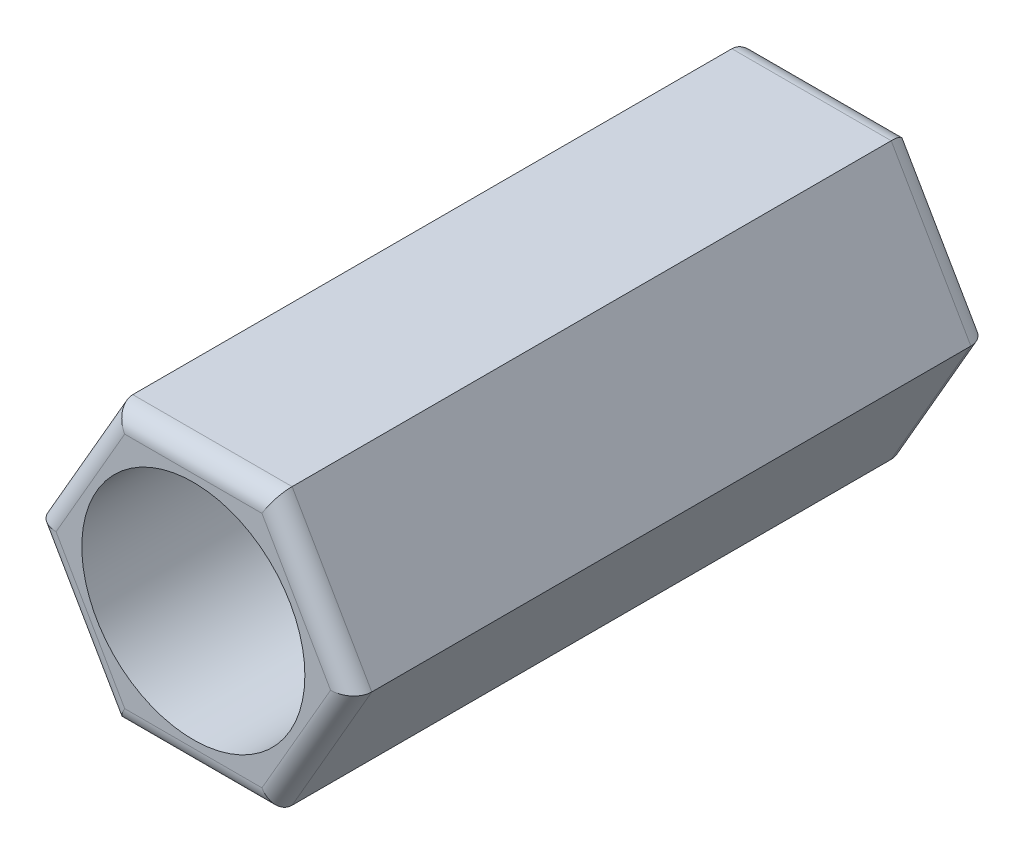
SolidWorks part; units mm, degrees
ref_plane "Front Plane" through (0, 0, 0) normal (0, 0, 1) x (1, 0, 0)
ref_plane "Top Plane" through (0, 0, 0) normal (0, 1, 0) x (1, 0, 0)
ref_plane "Right Plane" through (0, 0, 0) normal (1, 0, 0) x (0, 0, -1)
sketch "Sketch1" plane through (0, 0, 0) normal (0, 0, 1) x (1, 0, 0)
  line L1 (2.5, 0) -> (1.25, 2.1651)
  line L2 (1.25, 2.1651) -> (-1.25, 2.1651)
  line L3 (-1.25, 2.1651) -> (-2.5, 0)
  line L4 (-2.5, 0) -> (-1.25, -2.1651)
  line L5 (-1.25, -2.1651) -> (1.25, -2.1651)
  line L6 (1.25, -2.1651) -> (2.5, 0)
  circle A0 centre (0, 0) radius 2.1651 construction
  circle A1 centre (0, 0) radius 1.75
  dimension "D2" = 3.5
  dimension "D1" = 5
extrude "Boss-Extrude1" add sketch "Sketch1" along normal blind 10
fillet "Fillet5" radius 0.3 6 edges at (1.875, -1.0825, 10) (1.875, 1.0825, 10) (0, 2.1651, 10) (-1.875, 1.0825, 10) (-1.875, -1.0825, 10) (0, -2.1651, 10)
fillet "Fillet6" radius 0.3 6 edges at (0, -2.1651, 0) (-1.875, -1.0825, 0) (-1.875, 1.0825, 0) (1.875, 1.0825, 0) (0, 2.1651, 0) (1.875, -1.0825, 0)
